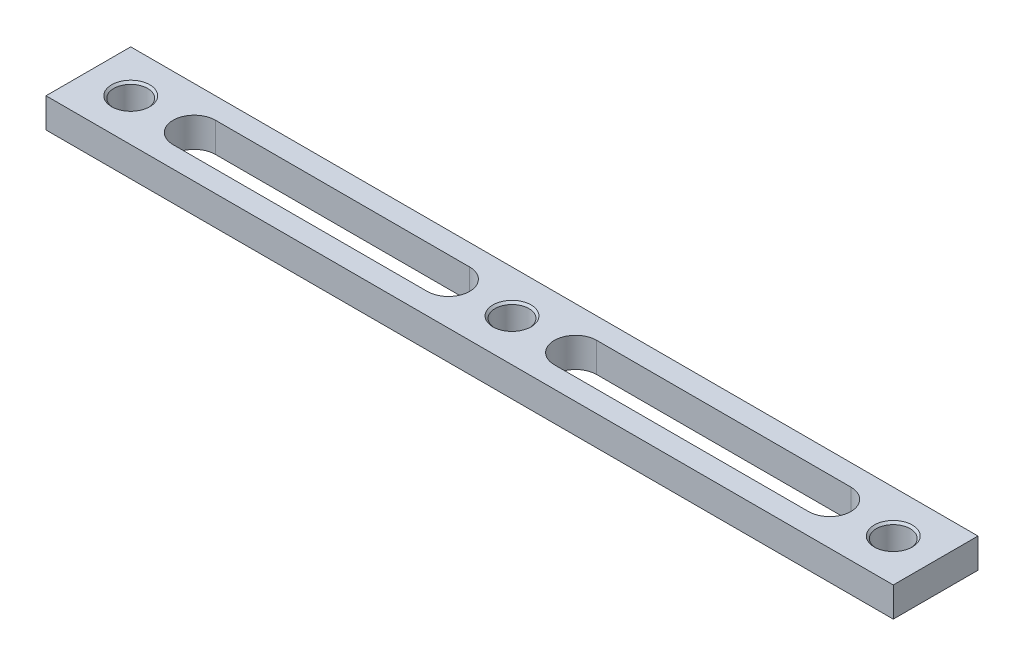
SolidWorks part; units mm, degrees
material "7075-T6, Płyta (SS)"
ref_plane "Płaszczyzna przednia" through (0, 0, 0) normal (0, 0, 1) x (1, 0, 0)
ref_plane "Płaszczyzna górna" through (0, 0, 0) normal (0, 1, 0) x (1, 0, 0)
ref_plane "Płaszczyzna prawa" through (0, 0, 0) normal (1, 0, 0) x (0, 0, -1)
sketch "Szkic1" plane through (0, 0, 0) normal (0, 1, 0) x (1, 0, 0)
  line L0 (-90, 0) -> (90, 0) construction
  line L1 (-100, -10) -> (100, -10)
  line L2 (-100, -10) -> (-100, 10)
  line L3 (-100, 10) -> (100, 10)
  line L4 (100, -10) -> (100, 10)
  line L5 (-100, -10) -> (100, 10) construction
  line L6 (-100, 10) -> (100, -10) construction
  line L7 (-75, 0) -> (-15, 0) construction
  line L8 (-75, 5) -> (-15, 5)
  line L9 (-75, -5) -> (-15, -5)
  line L10 (0, 10) -> (0, -10) construction
  line L11 (75, 0) -> (15, 0) construction
  line L12 (75, 5) -> (15, 5)
  line L13 (75, -5) -> (15, -5)
  arc A0 (-75, 5) -> (-75, -5) centre (-75, 0) ccw
  arc A1 (-15, -5) -> (-15, 5) centre (-15, 0) ccw
  arc A2 (75, 5) -> (75, -5) centre (75, 0) cw
  arc A3 (15, -5) -> (15, 5) centre (15, 0) cw
  point P0 (0, 0)
  point P6 (-90, 0)
  point P7 (90, 0)
  point P10 (-45, 0)
  point P21 (45, 0)
  dimension "D5" = 10
  dimension "D6" = 10
  dimension "D7" = 5
  dimension "D1" = 20
  dimension "D2" = 180
  dimension "D3" = 10
  dimension "D4" = 10
extrude "Dodanie-wyciągnięcie1" add sketch "Szkic1" along normal blind 7
sketch "Szkic2" plane through (0, 7, 0) normal (0, 1, 0) x (1, 0, 0)
  line L0 (-100, 0) -> (100, 0) construction
  line L1 (-100, 10) -> (-100, -10) construction
  line L2 (100, -10) -> (100, 10) construction
  point P6 (-90, 0)
  point P7 (0, 0)
  point P8 (90, 0)
  dimension "D1" = 10
  dimension "D2" = 10
hole_wizard "Otwory ustalające Ø8.0mm1" positions "Szkic3" profile "Szkic4" hole size "Ø8.0" standard "ISO" end condition up to next
sketch "Szkic3" plane through (0, 7, 0) normal (0, 1, 0) x (1, 0, 0)
  point P0 (-90, 0)
  point P3 (0, 0)
  point P6 (90, 0)
sketch "Szkic4" plane through (-90, 7, 0) normal (1, 0, 0) x (0, 0, 1)
  line L0 (0, 0) -> (0, 7)
  line L1 (0, 7) -> (4.5, 7)
  line L2 (4, 6.5) -> (4, 0.5)
  line L3 (4, 0.5) -> (4.5, 0)
  line L5 (4.5, 0) -> (0, 0)
  line L6 (-4, 0.5) -> (-4.5, 0) construction
  line L7 (4.5, 7) -> (4, 6.5)
  line L8 (-4.5, 7) -> (-4, 6.5) construction
  line L11 (0, -6.35) -> (0, 107.95) construction
  dimension "Średnica otworu na wylot" = 8
  dimension "Głębokość otworu na wylot" = 7
  dimension "Średnica zewnętrznego pogłębienia stożkowego" = 9
  dimension "Kąt zewnętrznego pogłębienia stożkowego" = 90
  dimension "Średnica wewnętrznego pogłębienia stożkowego" = 9
  dimension "Kąt wewnętrznego pogłębienia stożkowego" = 90
